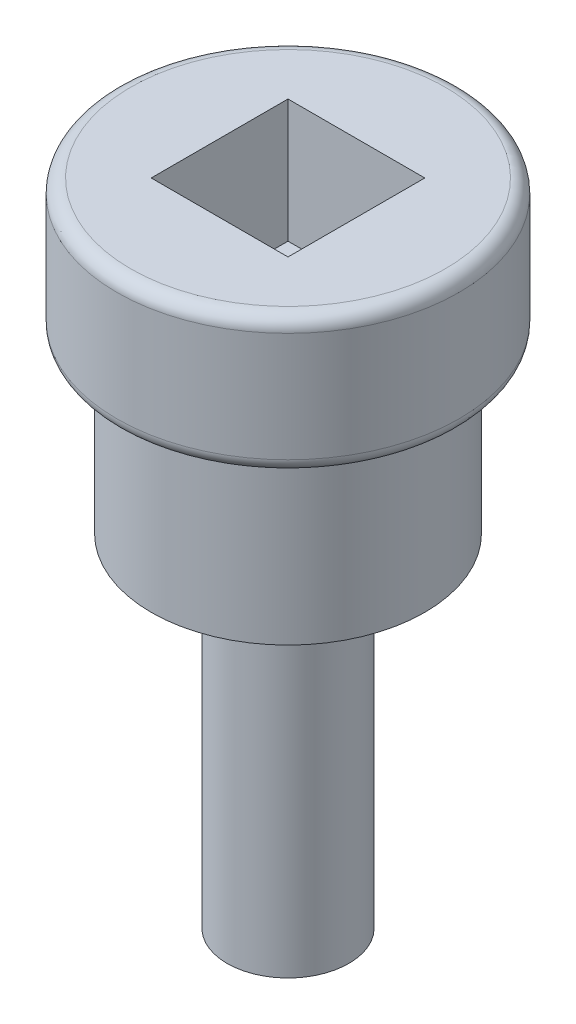
SolidWorks part; units mm, degrees
ref_plane "Front Plane" through (0, 0, 0) normal (0, 0, 1) x (1, 0, 0)
ref_plane "Top Plane" through (0, 0, 0) normal (0, 1, 0) x (1, 0, 0)
ref_plane "Right Plane" through (0, 0, 0) normal (1, 0, 0) x (0, 0, -1)
sketch "Sketch1" plane through (0, 0, 0) normal (0, 1, 0) x (1, 0, 0)
  circle A0 centre (0, 0) radius 2.54
  dimension "D1" = 5.08
extrude "Boss-Extrude1" add sketch "Sketch1" against normal blind 5.715 contours A0
sketch "Sketch2" plane through (0, 0, 0) normal (0, 1, 0) x (1, 0, 0)
  circle A0 centre (0, 0) radius 1.1303
  dimension "D1" = 2.2606
extrude "Boss-Extrude2" add sketch "Sketch2" against normal blind 12.065
sketch "Sketch3" plane through (0, 0, 0) normal (0, 1, 0) x (1, 0, 0)
  line L1 (-1.27, 1.27) -> (1.27, 1.27)
  line L2 (-1.27, 1.27) -> (-1.27, -1.27)
  line L3 (-1.27, -1.27) -> (1.27, -1.27)
  line L4 (1.27, 1.27) -> (1.27, -1.27)
  dimension "D1" = 2.54
  dimension "D2" = 2.54
  dimension "D3" = 1.27
  dimension "D4" = 1.27
sketch "Sketch4" plane through (0, 0, 0) normal (0, 1, 0) x (1, 0, 0)
  circle A0 centre (0, 0) radius 3.175
  dimension "D1" = 6.35
extrude "Boss-Extrude3" add sketch "Sketch4" against normal blind 2.54
extrude "Cut-Extrude1" cut sketch "Sketch3" against normal blind 2.286
fillet "Fillet1" radius 0.254 2 edges at (0, -2.54, 3.175) (0, 0, 3.175)
